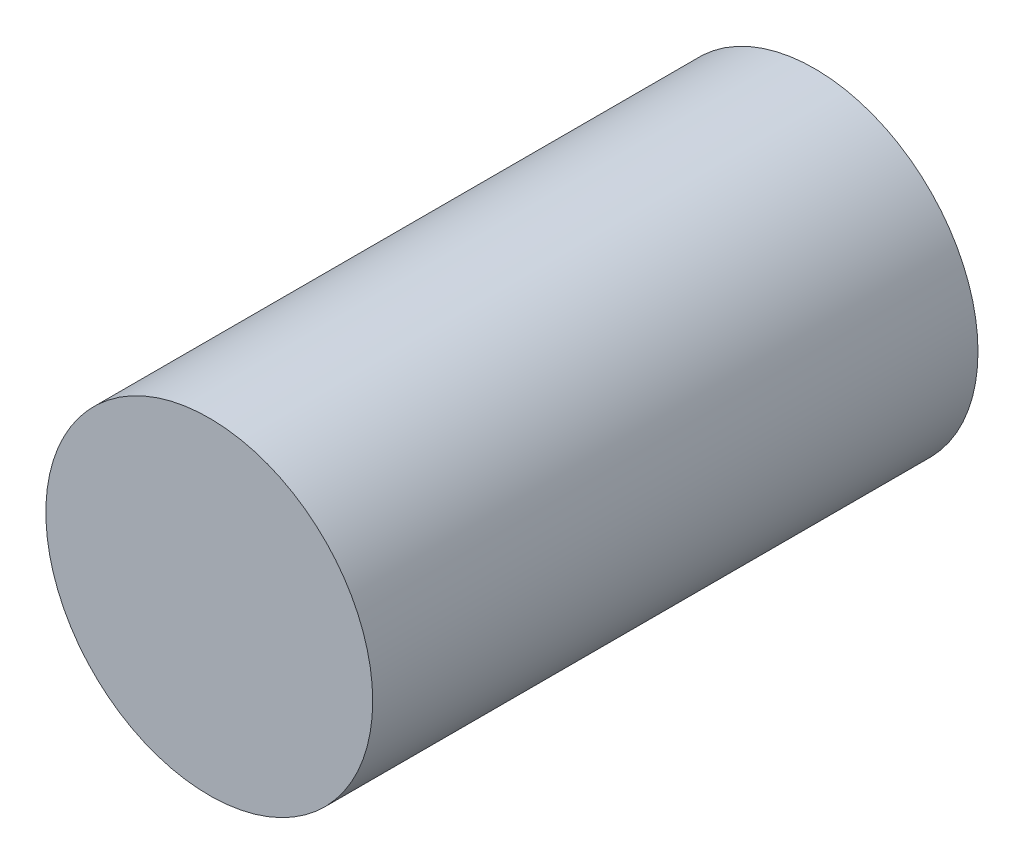
SolidWorks part; units mm, degrees
ref_plane "Front Plane" through (0, 0, 0) normal (0, 0, 1) x (1, 0, 0)
ref_plane "Top Plane" through (0, 0, 0) normal (0, 1, 0) x (1, 0, 0)
ref_plane "Right Plane" through (0, 0, 0) normal (1, 0, 0) x (0, 0, -1)
sketch "Sketch1" plane through (0, 0, 0) normal (0, 0, 1) x (1, 0, 0)
  circle A0 centre (0, 0) radius 13.5
  dimension "D1" = 27
extrude "Boss-Extrude1" add sketch "Sketch1" along normal blind 50
